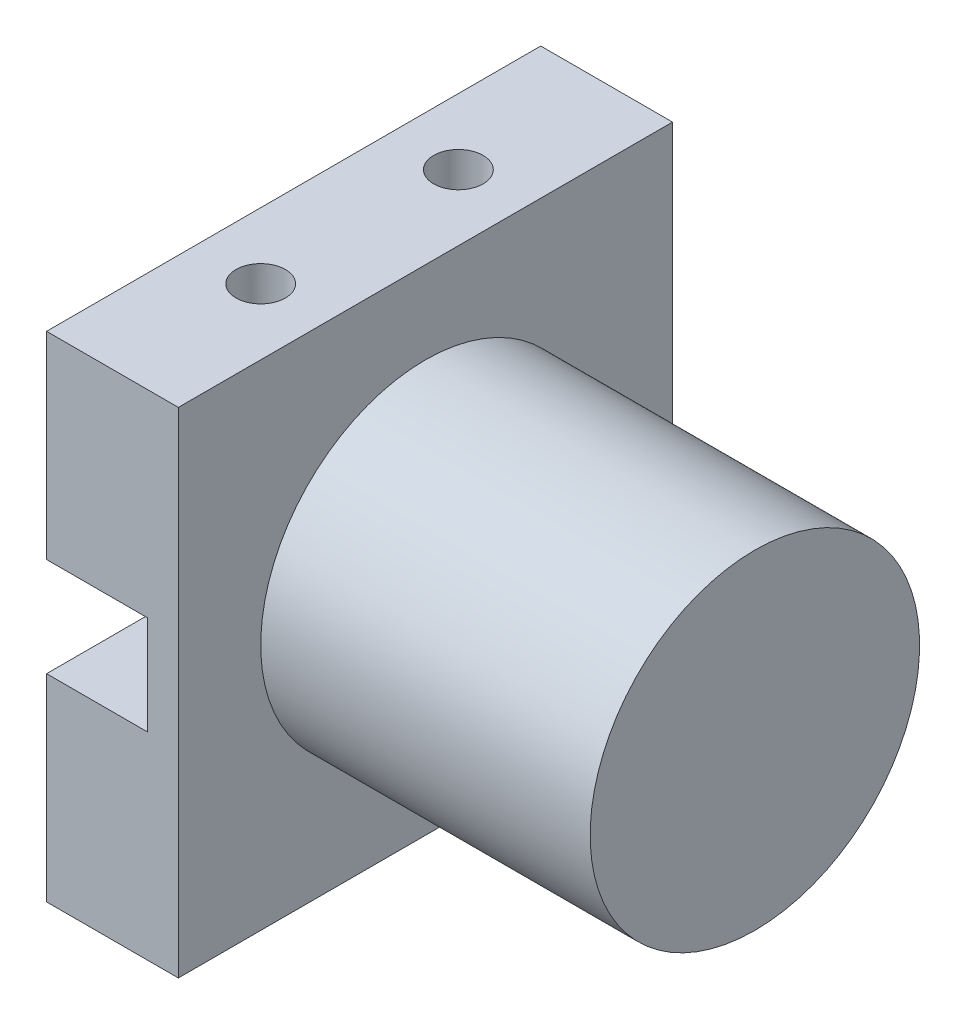
SolidWorks part; units mm, degrees
ref_plane "Front Plane" through (0, 0, 0) normal (0, 0, 1) x (1, 0, 0)
ref_plane "Top Plane" through (0, 0, 0) normal (0, 1, 0) x (1, 0, 0)
ref_plane "Right Plane" through (0, 0, 0) normal (1, 0, 0) x (0, 0, -1)
sketch "Sketch1" plane through (0, 0, 0) normal (0, 0, 1) x (1, 0, 0)
  line L0 (0, -15) -> (0, 15)
  line L1 (0, 15) -> (-8, 15)
  line L2 (-8, 15) -> (-8, 3)
  line L3 (-8, 3) -> (-1.8857, 3)
  line L4 (-1.8857, 3) -> (-1.8857, -3)
  line L5 (-1.8857, -3) -> (-8, -3)
  line L6 (-8, -3) -> (-8, -15)
  line L7 (-8, -15) -> (0, -15)
  point P4 (0, 0)
  dimension "D1" = 30
  dimension "D2" = 6
  dimension "D3" = 8
extrude "Boss-Extrude1" add sketch "Sketch1" along normal mid plane 30
sketch "Sketch2" plane through (0, 15, 0) normal (0, 1, 0) x (1, 0, 0)
  line L0 (0, 0) -> (-3.9497, 0) construction
  line L1 (0, -15) -> (0, 15) construction
  line L3 (0, 6) -> (-8, 6) construction
  line L4 (-8, -15) -> (-8, 15) construction
  circle A0 centre (-4, 6) radius 1.5
  circle A1 centre (-4, -6) radius 1.5
  point P6 (0, 0)
  dimension "D2" = 3
  dimension "D1" = 6
extrude "Cut-Extrude1" cut sketch "Sketch2" against normal through all
sketch "Sketch3" plane through (0, 0, 0) normal (1, 0, 0) x (0, 0, -1)
  circle A0 centre (0, 0) radius 10
  dimension "D1" = 20
extrude "Boss-Extrude2" add sketch "Sketch3" along normal blind 20
